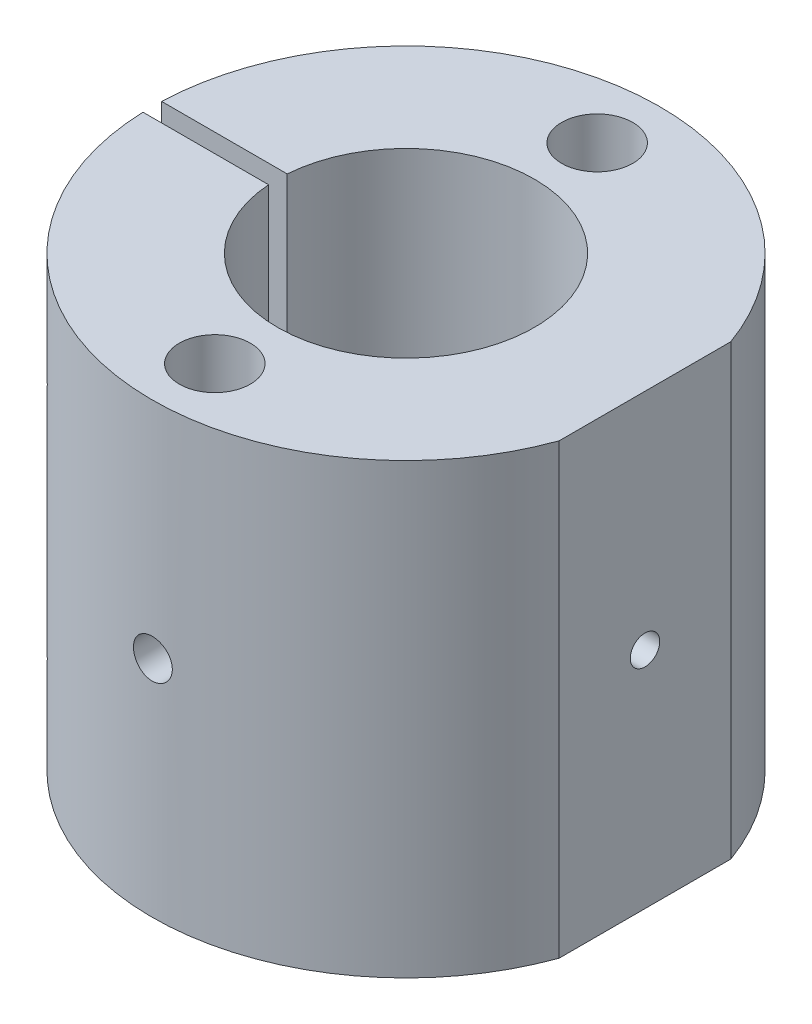
SolidWorks part; units mm, degrees
ref_plane "Front Plane" through (0, 0, 0) normal (0, 0, 1) x (1, 0, 0)
ref_plane "Top Plane" through (0, 0, 0) normal (0, 1, 0) x (1, 0, 0)
ref_plane "Right Plane" through (0, 0, 0) normal (1, 0, 0) x (0, 0, -1)
sketch "Sketch2" plane through (0, 0, 0) normal (0, 1, 0) x (1, 0, 0)
  circle A0 centre (0, 0) radius 10.922
  circle A1 centre (0, 0) radius 21.59
  dimension "D1" = 43.18
  dimension "D2" = 21.844
extrude "Boss-Extrude1" add sketch "Sketch2" along normal blind 38.1
sketch "Sketch3" plane through (0, 38.1, 0) normal (0, 1, 0) x (1, 0, 0)
  line L0 (0, 0) -> (-21.59, 0) construction
  line L1 (0, 0.7937) -> (-21.59, 0.7937)
  line L2 (0, -0.7937) -> (-21.59, -0.7938)
  line L3 (-21.59, 0.7937) -> (-21.59, -0.7938)
  line L4 (0, 0.7937) -> (0, -0.7937)
  circle A0 centre (0, 0) radius 21.59 construction
  dimension "D1" = 0.7937
  dimension "D2" = 0.7937
extrude "Cut-Extrude1" cut sketch "Sketch3" against normal up to next
sketch "Sketch4" plane through (0, 38.1, 0) normal (0, 1, 0) x (1, 0, 0)
  line L0 (0, -10.922) -> (0, -21.59) construction
  arc A0 (-10.8931, -0.7938) -> (-10.8931, 0.7937) centre (0, 0) ccw construction
  arc A1 (-21.5754, -0.7938) -> (-21.5754, 0.7937) centre (0, 0) ccw construction
  circle A2 centre (0, -16.256) radius 3.0226
  dimension "D1" = 6.0452
extrude "Cut-Extrude2" cut sketch "Sketch4" against normal up to next
ref_plane "Plane1" through (0, 0, 21.59) normal (0, 0, 1) x (1, 0, 0)
sketch "Sketch9" plane through (0, 0, 0.7937) normal (0, 0, -1) x (-1, 0, 0)
  line L0 (16.2343, 0) -> (16.2343, 38.1) construction
  line L1 (10.8931, 0) -> (21.5754, 0) construction
  line L2 (21.5754, 38.1) -> (10.8931, 38.1) construction
  circle A0 centre (16.2343, 29.1092) radius 1.0697 construction
  circle A1 centre (16.2343, 8.904) radius 1.0697 construction
hole_wizard "Tap Drill for M4x0.7 Tap1" positions "3DSketch4" profile "Sketch10" hole size "M4x0.7" standard "ANSI Metric"
sketch3d "3DSketch4"
  point P0 (-16.2343, 29.1092, 0.7938)
  point P3 (-16.2343, 8.904, 0.7938)
sketch "Sketch10" plane through (-16.2343, 29.1092, 0.7938) normal (1, 0, 0) x (0, 1, 0)
  line L0 (0, 0) -> (0, 13.4392)
  line L1 (0, 13.4392) -> (1.65, 13.4392)
  line L2 (1.65, 13.4392) -> (1.65, 0)
  line L5 (1.65, 0) -> (0, 0)
  line L11 (0, -6.35) -> (0, 107.95) construction
  dimension "Thru Hole Dia." = 3.3
  dimension "Thru Hole Depth" = 13.4392
sketch "Sketch11" plane through (0, 0, 21.59) normal (0, 0, 1) x (1, 0, 0)
  line L0 (0.0073, 0) -> (0.0073, 38.1) construction
  line L1 (-21.5754, 0) -> (21.59, 0) construction
  line L2 (21.59, 38.1) -> (-21.5754, 38.1) construction
  circle A0 centre (0.0073, 19.05) radius 1.65
  dimension "D1" = 3.3
extrude "Cut-Extrude5" cut sketch "Sketch11" against normal up to next
mirror "Mirror1" about plane through (0, 0, 0) normal (0, 0, 1) of "Cut-Extrude2", "Cut-Extrude5"
sketch "Sketch12" plane through (0, 38.1, 0) normal (0, 1, 0) x (1, 0, 0)
  line L0 (20.32, 7.2956) -> (20.32, -7.2956)
  arc A0 (-21.5754, -0.7938) -> (-21.5754, 0.7937) centre (0, 0) ccw construction
  arc A1 (20.32, -7.2956) -> (20.32, 7.2956) centre (0, 0) ccw
  arc A2 (-10.8931, -0.7938) -> (-10.8931, 0.7937) centre (0, 0) ccw construction
  dimension "D1" = 20.32
extrude "Cut-Extrude6" cut sketch "Sketch12" against normal up to next
sketch "Sketch13" plane through (20.32, 0, 0) normal (1, 0, 0) x (0, 0, -1)
  line L0 (0, 38.1) -> (0, 0) construction
  line L1 (7.2956, 38.1) -> (-7.2956, 38.1) construction
  line L2 (-7.2956, 0) -> (7.2956, 0) construction
  circle A0 centre (0, 19.05) radius 1.15 construction
  dimension "D1" = 2.3
hole_wizard "Tap Drill for M3x0.5 Tap2" positions "3DSketch5" profile "Sketch14" hole size "M3x0.5" standard "ANSI Metric"
sketch3d "3DSketch5"
  point P0 (20.32, 19.05, 0)
sketch "Sketch14" plane through (20.32, 19.05, 0) normal (0, 1, 0) x (0, 0, -1)
  line L0 (0, 0) -> (0, 5.3231)
  line L1 (0, 5.3231) -> (1.25, 4.572)
  line L2 (1.25, 4.572) -> (1.25, 0)
  line L5 (1.25, 0) -> (0, 0)
  line L10 (0, 5.3231) -> (-1.25, 4.572) construction
  line L11 (0, -6.35) -> (0, 107.95) construction
  dimension "Hole Dia." = 2.5
  dimension "Hole Depth" = 4.572
  dimension "Drill Angle" = 118
